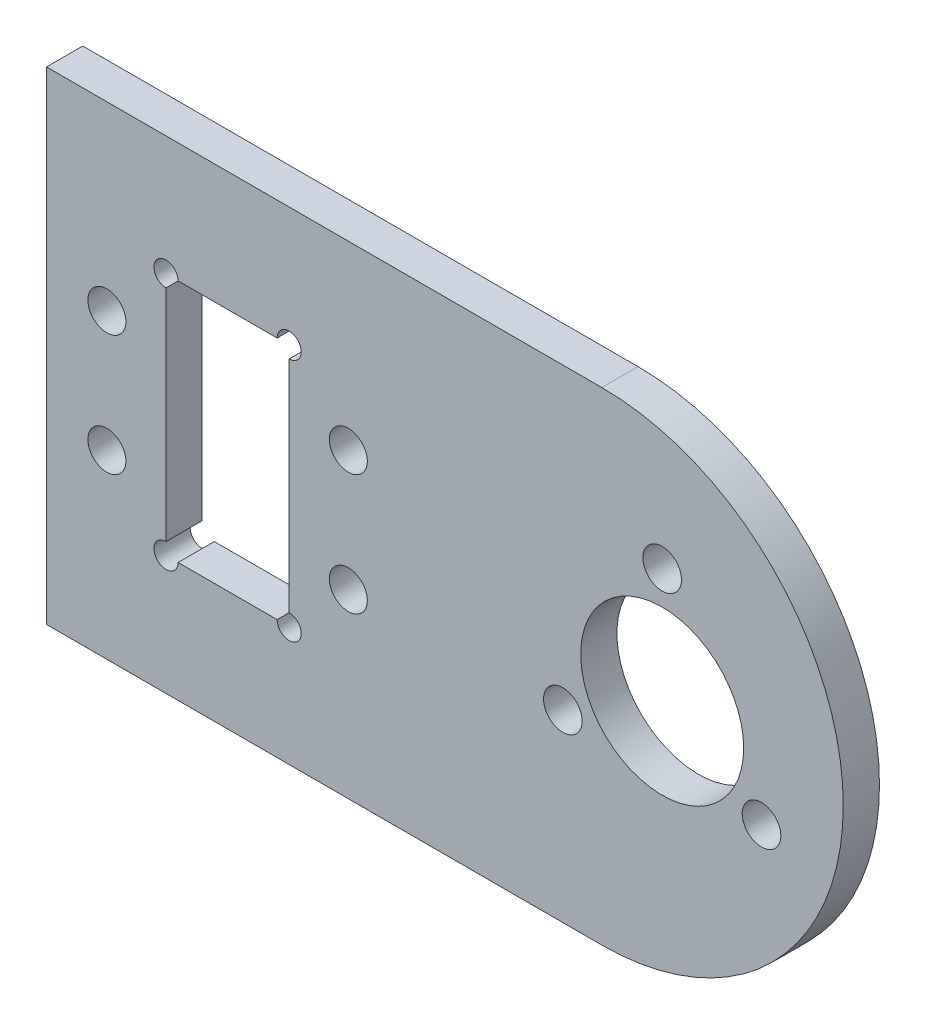
SolidWorks part; units mm, degrees
ref_plane "前视基准面" through (0, 0, 0) normal (0, 0, 1) x (1, 0, 0)
ref_plane "上视基准面" through (0, 0, 0) normal (0, 1, 0) x (1, 0, 0)
ref_plane "右视基准面" through (0, 0, 0) normal (1, 0, 0) x (0, 0, -1)
other "Configuration Table"
sketch "草图1" plane through (0, 0, 0) normal (0, 0, 1) x (1, 0, 0)
  line L0 (0, 0) -> (-46, 0)
  line L1 (-46, 0) -> (-46, -40)
  line L2 (-46, -40) -> (0, -40)
  line L3 (0, 0) -> (0, -40) construction
  arc A0 (0, -40) -> (0, 0) centre (0, -20) ccw
  point P6 (0, 0)
  point P7 (0, 0)
  dimension "D1" = 40
  dimension "D2" = 46
extrude "凸台-拉伸1" add sketch "草图1" along normal blind 3
sketch "草图2" plane through (0, 0, 3) normal (0, 0, 1) x (1, 0, 0)
  line L0 (-31, -9.9) -> (-31, -30.1) construction
  line L1 (-36.1, -9.9) -> (-25.9, -9.9)
  line L2 (-36.1, -9.9) -> (-36.1, -30.1)
  line L3 (-36.1, -30.1) -> (-25.9, -30.1)
  line L4 (-25.9, -9.9) -> (-25.9, -30.1)
  line L5 (-46, 0) -> (-46, -40) construction
  line L6 (-46, -20) -> (20, -20) construction
  line L7 (5, -20) -> (5, -0.6351) construction
  arc A0 (0, -40) -> (0, 0) centre (0, -20) ccw construction
  circle A1 centre (-41, -15) radius 1.575
  circle A2 centre (-41, -25) radius 1.575
  circle A3 centre (-21, -25) radius 1.575
  circle A4 centre (-21, -15) radius 1.575
  circle A5 centre (5, -20) radius 6.75
  circle A6 centre (5, -10.5) radius 1.6
  circle A7 centre (13.2272, -24.75) radius 1.6
  circle A8 centre (-3.2272, -24.75) radius 1.6
  point P27 (0, -25)
  point P28 (0, 0)
  point P29 (0, 0)
  point P34 (5, -20)
  point P35 (3.7685, -20)
  point P36 (5, -0.8953)
  point P37 (5, -0.6351)
  point P38 (13.2272, -24.75)
  dimension "D4" = 5
  dimension "D6" = 3.15
  dimension "D7" = 13.5
  dimension "D8" = 3.2
  dimension "D1" = 20.2
  dimension "D2" = 10.2
  dimension "D3" = 15
  dimension "D5" = 10
  dimension "D9" = 9.5
  dimension "D11" = 15
  dimension "D10" = 3
extrude "切除-拉伸1" cut sketch "草图2" against normal through all
sketch "草图3" plane through (0, 0, 3) normal (0, 0, 1) x (1, 0, 0)
  circle A0 centre (-25.9, -9.9) radius 1
  circle A1 centre (-25.9, -30.1) radius 1
  circle A2 centre (-36.1, -30.1) radius 1
  circle A3 centre (-36.1, -9.9) radius 1
  dimension "D1" = 2
extrude "切除-拉伸2" cut sketch "草图3" against normal through all
